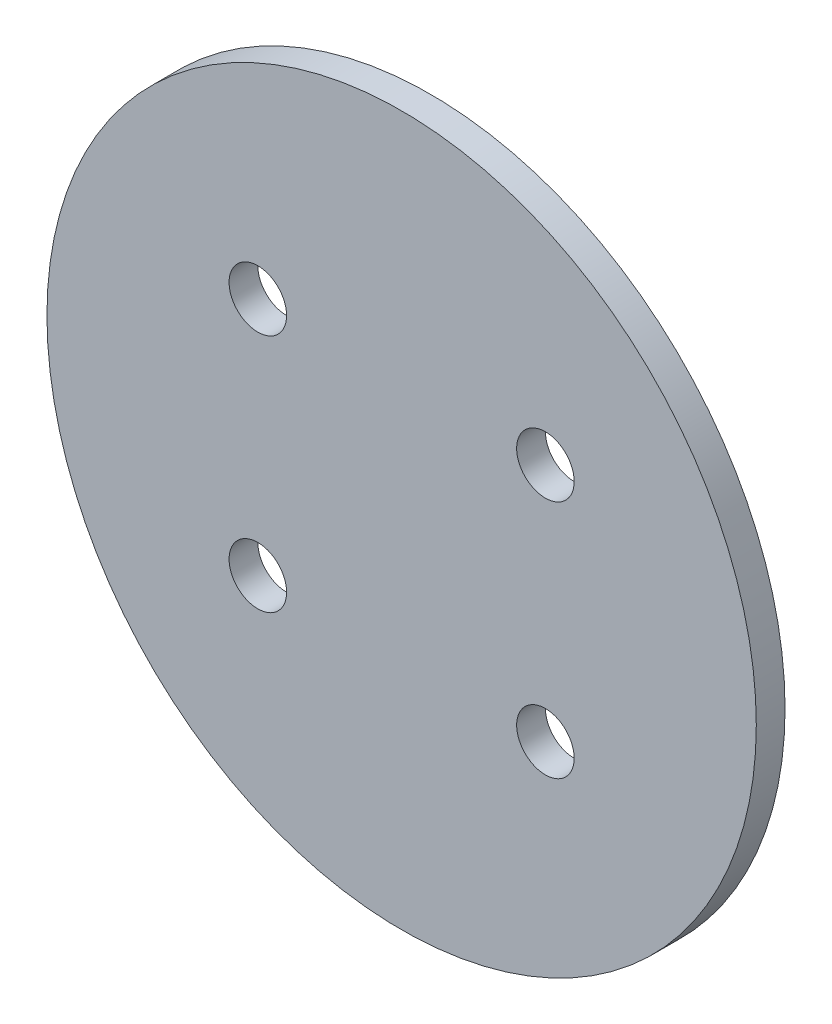
SolidWorks part; units mm, degrees
material "Acrylic (Medium-high impact)"
ref_plane "Front Plane" through (0, 0, 0) normal (0, 0, 1) x (1, 0, 0)
ref_plane "Top Plane" through (0, 0, 0) normal (0, 1, 0) x (1, 0, 0)
ref_plane "Right Plane" through (0, 0, 0) normal (1, 0, 0) x (0, 0, -1)
sketch "Model" plane through (0, 0, 0) normal (0, 0, 1) x (1, 0, 0)
  line L1 (15, -12.5) -> (-15, -12.5) construction
  line L2 (15, -12.5) -> (15, 12.5) construction
  line L3 (15, 12.5) -> (-15, 12.5) construction
  line L4 (-15, -12.5) -> (-15, 12.5) construction
  line L5 (15, -12.5) -> (-15, 12.5) construction
  line L6 (15, 12.5) -> (-15, -12.5) construction
  circle A0 centre (0, 0) radius 37
  circle A1 centre (-15, 12.5) radius 3
  circle A2 centre (-15, -12.5) radius 3
  circle A3 centre (15, -12.5) radius 3
  circle A4 centre (15, 12.5) radius 3
  dimension "D1" = 25
  dimension "D2" = 30
  dimension "D6" = 74
  dimension "D7" = 6
extrude "Boss-Extrude1" add sketch "Model" along normal blind 3
